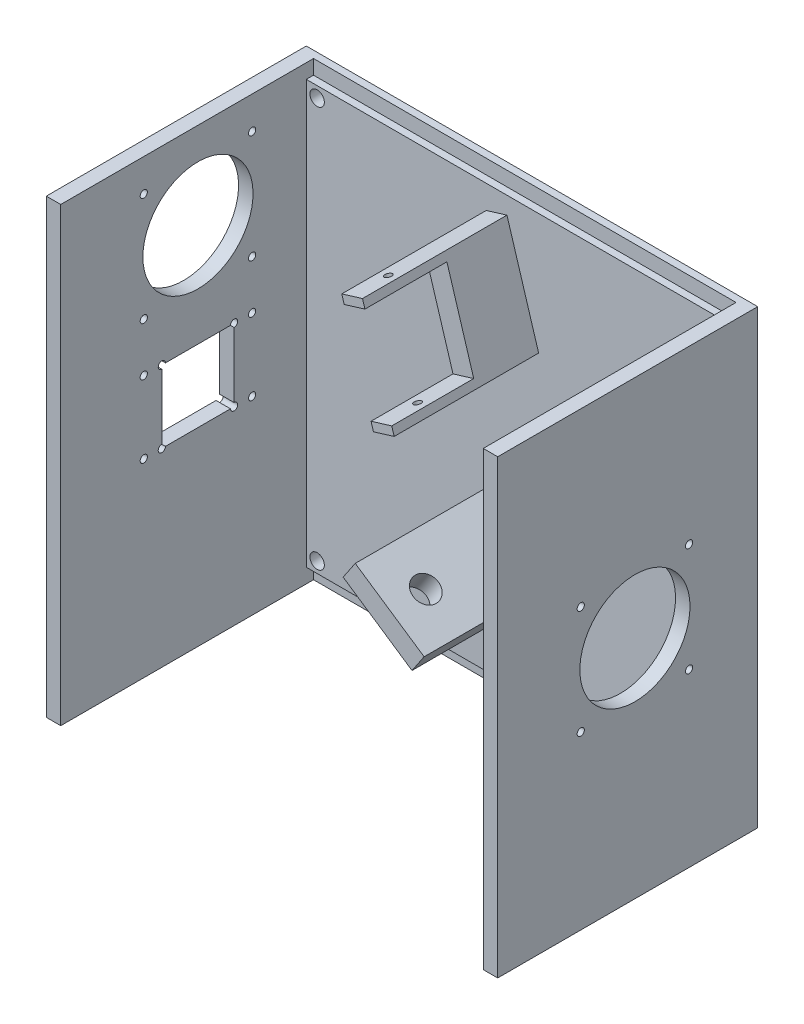
SolidWorks part; units mm, degrees
ref_plane "Ebene vorne" through (0, 0, 0) normal (0, 0, 1) x (1, 0, 0)
ref_plane "Ebene oben" through (0, 0, 0) normal (0, 1, 0) x (1, 0, 0)
ref_plane "Ebene rechts" through (0, 0, 0) normal (1, 0, 0) x (0, 0, -1)
sketch "Skizze1" plane through (0, 0, 0) normal (0, 0, 1) x (1, 0, 0)
  line L1 (0, 125) -> (125, 125)
  line L2 (0, 125) -> (0, 0)
  line L3 (0, 0) -> (125, 0)
  line L4 (125, 125) -> (125, 0)
  dimension "D1" = 125
  dimension "D2" = 125
extrude "Aufsatz-Linear austragen1" add sketch "Skizze1" along normal blind 2 contours L2 L1 L4 L3
sketch "Skizze2" plane through (0, 0, 2) normal (0, 0, 1) x (1, 0, 0)
  line L0 (0, 125) -> (0, 0) construction
  line L1 (4, 121) -> (121, 121)
  line L2 (4, 121) -> (4, 4)
  line L3 (4, 4) -> (121, 4)
  line L4 (121, 121) -> (121, 4)
  line L5 (0, 125) -> (125, 125) construction
  line L6 (0, 0) -> (125, 0) construction
  line L7 (125, 125) -> (125, 0) construction
  dimension "D1" = 4
  dimension "D2" = 4
  dimension "D3" = 4
  dimension "D4" = 4
extrude "Aufsatz-Linear austragen2" add sketch "Skizze2" along normal blind 2
sketch "Skizze3" plane through (0, 0, 4) normal (0, 0, 1) x (1, 0, 0)
  line L0 (121, 121) -> (4, 121) construction
  line L1 (4, 121) -> (4, 4) construction
  line L2 (4, 121) -> (4, 4) construction
  line L3 (4, 4) -> (121, 4) construction
  line L4 (121, 4) -> (121, 121) construction
  line L5 (121, 121) -> (4, 121) construction
  circle A0 centre (7, 118) radius 2
  circle A1 centre (7, 7) radius 2
  circle A2 centre (118, 7) radius 2
  circle A3 centre (118, 118) radius 2
  dimension "D1" = 3
  dimension "D3" = 3
  dimension "D5" = 3
  dimension "D2" = 3
  dimension "D4" = 3
  dimension "D6" = 3
  dimension "D7" = 3
  dimension "D8" = 3
extrude "Schnitt-Linear austragen1" cut sketch "Skizze3" against normal blind 32
sketch "Skizze4" plane through (0, 0, 4) normal (0, 0, 1) x (1, 0, 0)
  line L0 (121, 121) -> (121, 4) construction
  line L1 (4, 62.5) -> (121, 62.5) construction
  line L3 (4, 121) -> (4, 4) construction
  line L4 (4, 62.5) -> (90.7298, 121) construction
  line L5 (3.8274, 56.5) -> (121, 56.5) construction
  line L6 (121, 121) -> (4, 121) construction
  line L15 (4, 62.5) -> (90.7298, 4) construction
  line L16 (4, 4) -> (121, 4) construction
  line L17 (3.8274, 56.5) -> (3.8274, 68.5) construction
  line L18 (4, 62.5) -> (195.3449, 121) construction
  line L26 (3.8274, 68.5) -> (121, 68.5) construction
  line L31 (62.5953, 85.7783) -> (68.3331, 87.5325)
  line L32 (62.5953, 85.7783) -> (53.8241, 114.4675)
  line L33 (68.3331, 87.5325) -> (59.5619, 116.2217)
  line L34 (53.8241, 114.4675) -> (59.5619, 116.2217)
  line L35 (53.8241, 114.4675) -> (68.3331, 87.5325) construction
  line L37 (37.4248, 21.8614) -> (54.2006, 46.7326) construction
  line L38 (54.2006, 46.7326) -> (73.2684, 33.8711) construction
  line L39 (37.4248, 21.8614) -> (56.4926, 9) construction
  line L40 (56.4926, 9) -> (73.2684, 33.8711) construction
  line L41 (54.2006, 46.7326) -> (73.2684, 33.8711)
  line L42 (54.2006, 46.7326) -> (57.5557, 51.7068)
  line L43 (73.2684, 33.8711) -> (76.6236, 38.8454)
  line L44 (57.5557, 51.7068) -> (76.6236, 38.8454)
  line L45 (0, 125) -> (125, 125) construction
  point P11 (3.8274, 62.5)
  point P14 (61.0786, 101)
  point P27 (45.8127, 34.297)
  dimension "D1" = 34
  dimension "D2" = 34
  dimension "D3" = 12
  dimension "D4" = 17
  dimension "D5" = 6
  dimension "D6" = 30
  dimension "D7" = 24
  dimension "D8" = 30
  dimension "D9" = 23
  dimension "D10" = 6
  dimension "D11" = 5
extrude "Aufsatz-Linear austragen3" add sketch "Skizze4" along normal blind 40
sketch "Skizze7" plane through (0, 0, 44) normal (0, 0, 1) x (1, 0, 0)
  line L0 (54.4966, 112.268) -> (60.2344, 114.0222)
  line L1 (54.4966, 112.268) -> (61.9228, 87.9778)
  line L2 (60.2344, 114.0222) -> (67.6606, 89.732)
  line L3 (61.9228, 87.9778) -> (67.6606, 89.732)
  line L4 (53.8241, 114.4675) -> (62.5953, 85.7783) construction
  line L5 (68.3331, 87.5325) -> (59.5619, 116.2217) construction
  line L6 (57.3655, 113.1451) -> (56.693, 115.3446) construction
  line L7 (59.5619, 116.2217) -> (53.8241, 114.4675) construction
  line L8 (64.7917, 88.8549) -> (65.4642, 86.6554) construction
  line L9 (62.5953, 85.7783) -> (68.3331, 87.5325) construction
  dimension "D1" = 25.4
sketch "Skizze8" plane through (-27.4037, 89.6336, 0) normal (-0.2924, 0.9563, 0) x (0.9563, 0.2924, 0)
  line L0 (90.9393, -44) -> (90.9393, -4) construction
  line L1 (90.9393, -4) -> (84.9393, -4) construction
  circle A0 centre (87.9393, -34) radius 1
  dimension "D1" = 3
  dimension "D2" = 30
extrude "Schnitt-Linear austragen3" cut sketch "Skizze8" against normal blind 40
sketch "Skizze9" plane through (41.9683, 62.2206, 0) normal (0.5592, 0.829, 0) x (0.829, -0.5592, 0)
  line L0 (30.3018, -34) -> (18.8018, -34) construction
  line L1 (18.8018, -44) -> (18.8018, -4) construction
  line L2 (30.3018, -34) -> (41.8018, -34) construction
  line L3 (41.8018, -44) -> (41.8018, -4) construction
  line L4 (41.8018, -4) -> (18.8018, -4) construction
  circle A0 centre (30.3018, -34) radius 3.4931
  dimension "D1" = 30
extrude "Schnitt-Linear austragen4" cut sketch "Skizze9" against normal blind 20
sketch "Skizze10" plane through (0, 0, 2) normal (0, 0, 1) x (1, 0, 0)
  line L0 (0, 0) -> (125, 0) construction
  line L5 (121, 4) -> (121, 121) construction
  line L6 (125, 125) -> (121, 125)
  line L7 (125, 125) -> (125, 0)
  line L8 (125, 0) -> (121, 0)
  line L9 (121, 125) -> (121, 0)
  line L11 (4, 121) -> (4, 4) construction
  line L12 (0, 125) -> (4, 125)
  line L13 (0, 125) -> (0, 0)
  line L14 (0, 0) -> (4, 0)
  line L15 (4, 125) -> (4, 0)
extrude "Aufsatz-Linear austragen4" add sketch "Skizze10" along normal blind 70
sketch "Skizze11" plane through (125, 0, 0) normal (1, 0, 0) x (0, 0, -1)
  line L0 (-34, 125) -> (-34, 0) construction
  line L1 (-72, 125) -> (0, 125) construction
  line L2 (-72, 0) -> (0, 0) construction
  line L3 (-34, 62.5) -> (0, 62.5) construction
  line L4 (-49, 77.5) -> (-19, 77.5) construction
  line L5 (-19, 77.5) -> (-19, 47.5) construction
  line L6 (-19, 47.5) -> (-49, 47.5) construction
  line L7 (-49, 47.5) -> (-49, 77.5) construction
  line L8 (-49, 77.5) -> (-19, 47.5) construction
  line L9 (0, 125) -> (0, 0) construction
  circle A0 centre (-34, 62.5) radius 15.25
  circle A1 centre (-49, 47.5) radius 1
  circle A2 centre (-19, 47.5) radius 1
  circle A3 centre (-49, 77.5) radius 1
  circle A4 centre (-19, 77.5) radius 1
  point P10 (-34, 62.5)
  dimension "D1" = 30
  dimension "D2" = 30
  dimension "D3" = 34
extrude "Schnitt-Linear austragen5" cut sketch "Skizze11" against normal blind 10
sketch "Skizze12" plane through (0, 0, 0) normal (-1, 0, 0) x (0, 0, 1)
  line L0 (0, 101) -> (34, 101) construction
  line L1 (0, 125) -> (0, 0) construction
  line L2 (34, 125) -> (34, 0) construction
  line L3 (72, 125) -> (0, 125) construction
  line L4 (72, 0) -> (0, 0) construction
  line L5 (19, 116) -> (49, 116) construction
  line L6 (49, 116) -> (49, 86) construction
  line L7 (49, 86) -> (19, 86) construction
  line L8 (19, 86) -> (19, 116) construction
  line L9 (19, 116) -> (49, 86) construction
  line L10 (24, 72.5) -> (44, 52.5) construction
  line L11 (24, 72.5) -> (44, 72.5)
  line L12 (24, 72.5) -> (24, 52.5)
  line L13 (24, 52.5) -> (44, 52.5)
  line L14 (44, 72.5) -> (44, 52.5)
  line L15 (19, 72.5) -> (49, 72.5) construction
  line L16 (49, 72.5) -> (49, 52.5) construction
  line L17 (49, 52.5) -> (19, 52.5) construction
  line L18 (19, 52.5) -> (19, 72.5) construction
  line L19 (19, 72.5) -> (49, 52.5) construction
  circle A0 centre (34, 101) radius 15.25
  circle A1 centre (19, 116) radius 1
  circle A2 centre (49, 116) radius 1
  circle A3 centre (49, 86) radius 1
  circle A4 centre (19, 86) radius 1
  circle A5 centre (19, 72.5) radius 1
  circle A6 centre (49, 72.5) radius 1
  circle A7 centre (49, 52.5) radius 1
  circle A8 centre (19, 52.5) radius 1
  point P10 (34, 101)
  point P16 (34, 62.5)
  point P24 (34, 62.5)
  dimension "D4" = 24
  dimension "D1" = 30
  dimension "D2" = 30
  dimension "D3" = 34
  dimension "D5" = 20
  dimension "D6" = 20
  dimension "D7" = 30
  dimension "D8" = 20
extrude "Schnitt-Linear austragen6" cut sketch "Skizze12" against normal blind 12
sketch "Skizze13" plane through (0, 0, 0) normal (-1, 0, 0) x (0, 0, 1)
  line L0 (44, 72.5) -> (24, 72.5) construction
  line L1 (44, 52.5) -> (44, 72.5) construction
  line L2 (24, 52.5) -> (44, 52.5) construction
  circle A0 centre (24, 52.5) radius 1
  circle A1 centre (44, 52.5) radius 1
  circle A2 centre (24, 72.5) radius 1
  circle A3 centre (44, 72.5) radius 1
extrude "Schnitt-Linear austragen7" cut sketch "Skizze13" against normal blind 10
extrude "Schnitt-Linear austragen8" cut sketch "Skizze7" against normal blind 22.7
